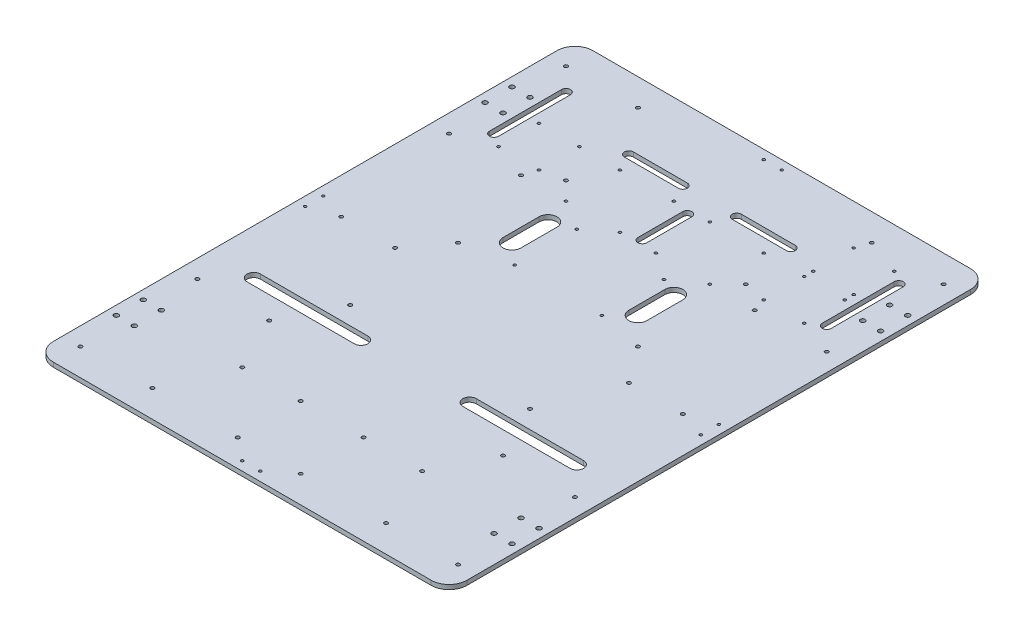
SolidWorks part; units mm, degrees
ref_plane "前视基准面" through (0, 0, 0) normal (0, 0, 1) x (1, 0, 0)
ref_plane "上视基准面" through (0, 0, 0) normal (0, 1, 0) x (1, 0, 0)
ref_plane "右视基准面" through (0, 0, 0) normal (1, 0, 0) x (0, 0, -1)
sketch "草图1" plane through (0, 0, 0) normal (0, 1, 0) x (1, 0, 0)
  line L1 (210, -300) -> (-210, -300)
  line L2 (230, -280) -> (230, 280)
  line L3 (210, 300) -> (-210, 300)
  line L4 (-230, -280) -> (-230, 280)
  line L5 (230, -300) -> (-230, 300) construction
  line L6 (230, 300) -> (-230, -300) construction
  arc A0 (210, 300) -> (230, 280) centre (210, 280) cw
  arc A1 (230, -280) -> (210, -300) centre (210, -280) cw
  arc A2 (-210, -300) -> (-230, -280) centre (-210, -280) cw
  arc A3 (-230, 280) -> (-210, 300) centre (-210, 280) cw
  circle A4 centre (100, -200) radius 2
  circle A5 centre (100, -80) radius 2
  circle A6 centre (100, 40) radius 2
  circle A7 centre (100, 160) radius 2
  point P0 (0, 0)
  dimension "D1" = 20
  dimension "D2" = 4
extrude "主底盘" add sketch "草图1" along normal blind 5
sketch "草图2" plane through (0, 5, 0) normal (0, 1, 0) x (1, 0, 0)
  circle A0 centre (10, 290) radius 1.5
  circle A3 centre (-10, 290) radius 1.5
  circle A4 centre (-10, -290) radius 1.5
  circle A5 centre (10, -290) radius 1.5
  circle A7 centre (-220, 10) radius 1.5
  circle A9 centre (-220, -10) radius 1.5
  circle A10 centre (220, 10) radius 1.5
  circle A11 centre (220, -10) radius 1.5
extrude "寻线模块定位孔" cut sketch "草图2" against normal through all
sketch "草图3" plane through (0, 5, 0) normal (0, 1, 0) x (1, 0, 0)
  circle A0 centre (-210, 270) radius 2
  circle A1 centre (-130, 270) radius 2
  circle A2 centre (-210, 140) radius 2
  circle A3 centre (-130, 140) radius 2
  circle A4 centre (130, 270) radius 2
  circle A6 centre (210, 270) radius 2
  circle A7 centre (130, 140) radius 2
  circle A8 centre (210, 140) radius 2
  circle A9 centre (-210, -140) radius 2
  circle A10 centre (-130, -140) radius 2
  circle A12 centre (-210, -270) radius 2
  circle A14 centre (-130, -270) radius 2
  circle A15 centre (130, -140) radius 2
  circle A16 centre (210, -140) radius 2
  circle A17 centre (130, -270) radius 2
  circle A18 centre (210, -270) radius 2
  dimension "D1" = 2
  dimension "D4" = 2
  dimension "D5" = 2
  dimension "D6" = 2
  dimension "D7" = 2
  dimension "D8" = 2
  dimension "D2" = 2
  dimension "D3" = 2
extrude "铝横材定位孔" cut sketch "草图3" against normal through all
sketch "草图4" plane through (0, 5, 0) normal (0, 1, 0) x (1, 0, 0)
  circle A0 centre (-100, -200) radius 2
  circle A1 centre (-100, -80) radius 2
  circle A2 centre (-100, 40) radius 2
  circle A3 centre (-100, 160) radius 2
  dimension "D1" = 4
extrude "铝竖材定位孔" cut sketch "草图4" against normal through all
sketch "草图5" plane through (0, 5, 0) normal (0, 1, 0) x (1, 0, 0)
  circle A0 centre (220, -220) radius 2.6
  circle A1 centre (200, -220) radius 2.6
  circle A2 centre (220, -190) radius 2.6
  circle A3 centre (200, -190) radius 2.6
  circle A5 centre (-200, -220) radius 2.6
  circle A6 centre (-220, -220) radius 2.6
  circle A7 centre (-200, -190) radius 2.6
  circle A8 centre (-220, -190) radius 2.6
  circle A9 centre (200, 190) radius 2.6
  circle A10 centre (220, 190) radius 2.6
  circle A11 centre (200, 220) radius 2.6
  circle A12 centre (220, 220) radius 2.6
  circle A14 centre (-200, 190) radius 2.6
  circle A15 centre (-220, 190) radius 2.6
  circle A16 centre (-200, 220) radius 2.6
  circle A17 centre (-220, 220) radius 2.6
  dimension "D1" = 2
  dimension "D3" = 2
  dimension "D5" = 2
  dimension "D2" = 2
  dimension "D4" = 2
extrude "电机支架定位孔" cut sketch "草图5" against normal through all
sketch "草图6" plane through (0, 5, 0) normal (0, 1, 0) x (1, 0, 0)
  circle A0 centre (-35, -270) radius 2
  circle A1 centre (35, -270) radius 2
  circle A2 centre (35, -200) radius 2
  circle A3 centre (-35, -200) radius 2
  dimension "D1" = 2
  dimension "D2" = 2
  dimension "D3" = 2
extrude "机械臂定位孔" cut sketch "草图6" against normal through all
sketch "草图7" plane through (0, 5, 0) normal (0, 1, 0) x (1, 0, 0)
  circle A0 centre (50, 50) radius 1.5
  circle A1 centre (-47, 50) radius 1.5
  circle A2 centre (50, 119) radius 1.5
  circle A3 centre (-47, 119) radius 1.5
  dimension "D1" = 2
  dimension "D2" = 2
  dimension "D3" = 2
extrude "主板固定位置" cut sketch "草图7" against normal through all
sketch "草图8" plane through (0, 5, 0) normal (0, 1, 0) x (1, 0, 0)
  circle A0 centre (80, 140) radius 1.5
  circle A2 centre (20, 140) radius 1.5
  circle A3 centre (80, 200) radius 1.5
  circle A4 centre (20, 200) radius 1.5
  circle A6 centre (-20, 140) radius 1.5
  circle A8 centre (-80, 140) radius 1.5
  circle A9 centre (-20, 200) radius 1.5
  circle A10 centre (-80, 200) radius 1.5
  dimension "D1" = 2
  dimension "D4" = 2
  dimension "D2" = 2
  dimension "D3" = 2
  dimension "D5" = 2
  dimension "D6" = 2
extrude "分电板固定位置" cut sketch "草图8" against normal through all
sketch "草图9" plane through (0, 5, 0) normal (0, 1, 0) x (1, 0, 0)
  circle A0 centre (170, 155) radius 1.5
  circle A1 centre (125, 155) radius 1.5
  circle A2 centre (125, 200) radius 1.5
  circle A3 centre (170, 200) radius 1.5
  circle A4 centre (170, 210) radius 1.5
  circle A5 centre (170, 255) radius 1.5
  circle A11 centre (125, 210) radius 1.5
  circle A12 centre (125, 255) radius 1.5
  circle A13 centre (-125, 155) radius 1.5
  circle A14 centre (-170, 155) radius 1.5
  circle A15 centre (-125, 200) radius 1.5
  circle A16 centre (-170, 200) radius 1.5
  dimension "D1" = 2
  dimension "D4" = 2
  dimension "D7" = 2
  dimension "D2" = 2
  dimension "D3" = 2
  dimension "D5" = 2
  dimension "D6" = 2
  dimension "D8" = 2
  dimension "D9" = 2
extrude "电机驱动模块固定位置" cut sketch "草图9" against normal through all
sketch "草图10" plane through (0, 5, 0) normal (0, 1, 0) x (1, 0, 0)
  line L0 (185, 165) -> (185, 245) construction
  line L1 (180, 165) -> (180, 245)
  line L2 (190, 165) -> (190, 245)
  line L3 (-185, 165) -> (-185, 245) construction
  line L8 (0, 145) -> (0, 195) construction
  line L9 (-5, 145) -> (-5, 195)
  line L10 (5, 145) -> (5, 195)
  line L15 (70, 70) -> (70, 110) construction
  line L16 (60, 70) -> (60, 110)
  line L17 (80, 70) -> (80, 110)
  line L18 (-70, 70) -> (-70, 110) construction
  line L19 (-80, 70) -> (-80, 110)
  line L20 (-60, 70) -> (-60, 110)
  line L21 (90, 220) -> (30, 220) construction
  line L22 (90, 215) -> (30, 215)
  line L23 (90, 225) -> (30, 225)
  line L24 (-30, 220) -> (-90, 220) construction
  line L25 (-30, 215) -> (-90, 215)
  line L26 (-30, 225) -> (-90, 225)
  line L27 (-190, 165) -> (-190, 245)
  line L28 (-180, 165) -> (-180, 245)
  line L29 (179.6741, -107.5) -> (60.3259, -107.5) construction
  line L30 (179.6741, -115) -> (60.3259, -115)
  line L31 (179.6741, -100) -> (60.3259, -100)
  line L32 (-60.3259, -107.5) -> (-179.6741, -107.5) construction
  line L35 (-60.3259, -115) -> (-179.6741, -115)
  line L38 (-60.3259, -100) -> (-179.6741, -100)
  arc A0 (180, 165) -> (190, 165) centre (185, 165) ccw
  arc A1 (190, 245) -> (180, 245) centre (185, 245) ccw
  arc A6 (-5, 145) -> (5, 145) centre (0, 145) ccw
  arc A7 (5, 195) -> (-5, 195) centre (0, 195) ccw
  arc A10 (60, 70) -> (80, 70) centre (70, 70) ccw
  arc A13 (80, 110) -> (60, 110) centre (70, 110) ccw
  arc A14 (-80, 70) -> (-60, 70) centre (-70, 70) ccw
  arc A15 (-60, 110) -> (-80, 110) centre (-70, 110) ccw
  arc A16 (90, 215) -> (90, 225) centre (90, 220) ccw
  arc A17 (30, 225) -> (30, 215) centre (30, 220) ccw
  arc A18 (-30, 215) -> (-30, 225) centre (-30, 220) ccw
  arc A19 (-90, 225) -> (-90, 215) centre (-90, 220) ccw
  arc A20 (-190, 165) -> (-180, 165) centre (-185, 165) ccw
  arc A21 (-180, 245) -> (-190, 245) centre (-185, 245) ccw
  arc A22 (179.6741, -115) -> (179.6741, -100) centre (179.6741, -107.5) ccw
  arc A23 (60.3259, -100) -> (60.3259, -115) centre (60.3259, -107.5) ccw
  arc A30 (-60.3259, -115) -> (-60.3259, -100) centre (-60.3259, -107.5) ccw
  arc A31 (-179.6741, -100) -> (-179.6741, -115) centre (-179.6741, -107.5) ccw
  point P2 (185, 205)
  point P12 (-185, 205)
  point P18 (0, 170)
  point P23 (70, 90)
  point P31 (-70, 90)
  point P37 (60, 220)
  point P45 (-60, 220)
  point P51 (120, -107.5)
  point P60 (-120, -107.5)
  dimension "D1" = 2
  dimension "D4" = 2
  dimension "D2" = 2
  dimension "D3" = 2
extrude "槽" cut sketch "草图10" against normal through all and the other way through all
sketch "草图11" plane through (0, 5, 0) normal (0, 1, 0) x (1, 0, 0)
  circle A0 centre (130, 0) radius 2
  circle A1 centre (190, 0) radius 2
  circle A2 centre (-130, 0) radius 2
  circle A3 centre (-190, 0) radius 2
  dimension "D1" = 2
  dimension "D2" = 2
  dimension "D3" = 2
extrude "加固铝材定位孔" cut sketch "草图11" against normal through all
